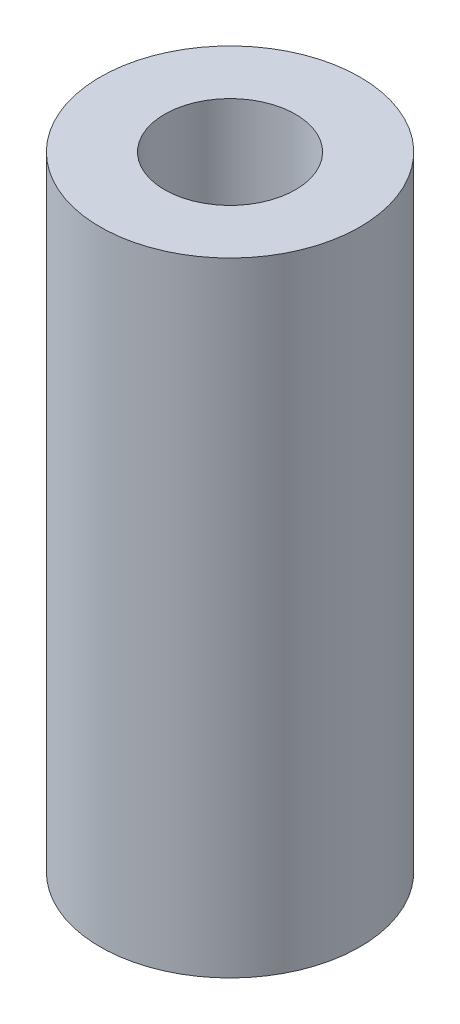
SolidWorks part; units mm, degrees
ref_plane "Front Plane" through (0, 0, 0) normal (0, 0, 1) x (1, 0, 0)
ref_plane "Top Plane" through (0, 0, 0) normal (0, 1, 0) x (1, 0, 0)
ref_plane "Right Plane" through (0, 0, 0) normal (1, 0, 0) x (0, 0, -1)
sketch "Sketch2" plane through (0, 0, 0) normal (0, 1, 0) x (1, 0, 0)
  circle A1 centre (0, 0) radius 15.875
  dimension "D1" = 31.75
extrude "Boss-Extrude1" add sketch "Sketch2" along normal mid plane 76.2
hole_wizard "Hole1" positions "Sketch3" profile "Sketch4" legacy end condition through all
sketch "Sketch3" plane through (0, 38.1, 0) normal (0, 1, 0) x (1, 0, 0)
  point P0 (0, 0)
sketch "Sketch4" plane through (0, 38.1, 0) normal (1, 0, 0) x (0, 0, 1)
  line L0 (0, 0) -> (0, 76.2)
  line L1 (0, 76.2) -> (8.001, 76.2)
  line L2 (8.001, 76.2) -> (8.001, 0)
  line L3 (8.001, 0) -> (0, 0)
  line L4 (0, 110) -> (0, -10) construction
  dimension "Diameter" = 16.002
  dimension "Depth" = 76.2
